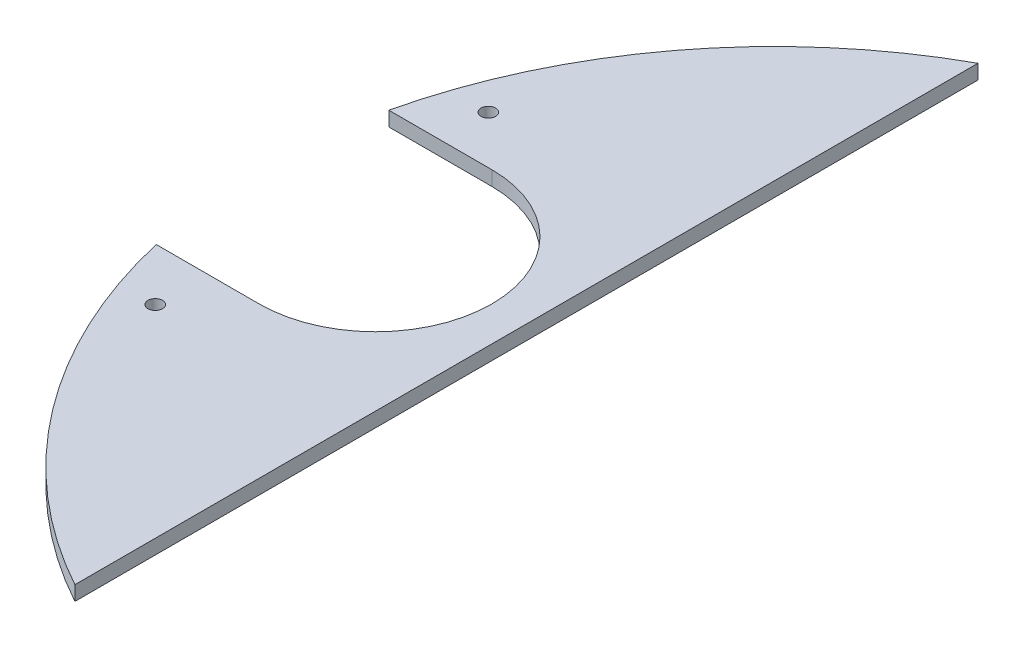
SolidWorks part; units mm, degrees
ref_plane "Front Plane" through (0, 0, 0) normal (0, 0, 1) x (1, 0, 0)
ref_plane "Top Plane" through (0, 0, 0) normal (0, 1, 0) x (1, 0, 0)
ref_plane "Right Plane" through (0, 0, 0) normal (1, 0, 0) x (0, 0, -1)
sketch "Sketch1" plane through (0, 0, 0) normal (0, 1, 0) x (1, 0, 0)
  line L0 (0, -112.5) -> (0, 0) construction
  line L1 (-80, 112.5) -> (100, 112.5)
  line L3 (-80, -112.5) -> (100, -112.5)
  line L4 (100, 112.5) -> (100, -112.5)
  line L5 (0, 0) -> (0, 112.5) construction
  arc A0 (-80, 112.5) -> (-80, -112.5) centre (-80, 0) ccw
  dimension "D1" = 100
  dimension "D4" = 112.5
  dimension "D2" = 80
  dimension "D3" = 225
extrude "Boss-Extrude1" add sketch "Sketch1" against normal blind 3.175
sketch "Sketch2" plane through (0, 0, 0) normal (0, 1, 0) x (1, 0, 0)
  line L0 (36.144, -74.2188) -> (36.144, -67.8688) construction
  line L1 (52.019, 0) -> (52.019, -89.9668) construction
  line L2 (11.887, -89.9668) -> (92.151, -89.9668)
  line L3 (11.887, -89.9668) -> (11.887, -102.9208)
  line L4 (11.887, -102.9208) -> (92.151, -102.9208)
  line L5 (92.151, -89.9668) -> (92.151, -102.9208)
  line L6 (11.887, 89.9668) -> (92.151, 89.9668)
  line L7 (11.887, 89.9668) -> (11.887, 102.9208)
  line L8 (11.887, 102.9208) -> (92.151, 102.9208)
  line L9 (92.151, 89.9668) -> (92.151, 102.9208)
  line L10 (52.019, 0) -> (52.019, 89.9668) construction
  line L11 (36.144, -67.8688) -> (36.144, -61.5188) construction
  line L12 (36.144, -61.5188) -> (36.144, -55.1688) construction
  line L13 (36.144, -55.1688) -> (36.144, -48.8188) construction
  line L14 (36.144, -48.8188) -> (36.144, -42.4688) construction
  line L15 (36.144, -42.4688) -> (36.144, -36.1188) construction
  line L16 (67.894, -74.2188) -> (67.894, -67.8688) construction
  line L17 (67.894, -67.8688) -> (67.894, -61.5188) construction
  line L18 (67.894, -61.5188) -> (67.894, -55.1688) construction
  line L19 (67.894, -55.1688) -> (67.894, -48.8188) construction
  line L20 (67.894, -48.8188) -> (67.894, -42.4688) construction
  line L21 (67.894, -42.4688) -> (67.894, -36.1188) construction
  line L22 (36.144, -74.2188) -> (67.894, -74.2188) construction
  line L23 (36.144, -36.1188) -> (67.894, -36.1188) construction
  line L24 (36.144, 36.1188) -> (36.144, 42.4688) construction
  line L25 (36.144, 42.4688) -> (36.144, 48.8188) construction
  line L26 (36.144, 48.8188) -> (36.144, 55.1688) construction
  line L27 (36.144, 55.1688) -> (36.144, 61.5188) construction
  line L28 (36.144, 61.5188) -> (36.144, 67.8688) construction
  line L29 (36.144, 67.8688) -> (36.144, 74.2188) construction
  line L30 (67.894, 36.1188) -> (67.894, 42.4688) construction
  line L31 (67.894, 42.4688) -> (67.894, 48.8188) construction
  line L32 (67.894, 48.8188) -> (67.894, 55.1688) construction
  line L33 (67.894, 55.1688) -> (67.894, 61.5188) construction
  line L34 (67.894, 61.5188) -> (67.894, 67.8688) construction
  line L35 (67.894, 67.8688) -> (67.894, 74.2188) construction
  line L36 (36.144, 74.2188) -> (67.894, 74.2188) construction
  line L37 (36.144, 36.1188) -> (67.894, 36.1188) construction
  line L38 (36.144, 55.1688) -> (52.019, 55.1688) construction
  line L39 (52.019, 55.1688) -> (67.894, 55.1688) construction
  line L40 (0, -112.5) -> (0, 112.5) construction
  line L41 (0, 0) -> (52.019, 0) construction
  line L42 (100, 112.5) -> (-80, 112.5) construction
  line L43 (-80, -112.5) -> (100, -112.5) construction
  circle A1 centre (36.144, -74.2188) radius 1.5875
  circle A2 centre (36.144, -67.8688) radius 1.5875
  circle A3 centre (36.144, -61.5188) radius 1.5875
  circle A4 centre (36.144, -55.1688) radius 1.5875
  circle A5 centre (36.144, -48.8188) radius 1.5875
  circle A6 centre (36.144, -42.4688) radius 1.5875
  circle A7 centre (36.144, -36.1188) radius 1.5875
  circle A8 centre (67.894, -74.2188) radius 1.5875
  circle A9 centre (67.894, -67.8688) radius 1.5875
  circle A10 centre (67.894, -61.5188) radius 1.5875
  circle A11 centre (67.894, -55.1688) radius 1.5875
  circle A12 centre (67.894, -48.8188) radius 1.5875
  circle A13 centre (67.894, -42.4688) radius 1.5875
  circle A14 centre (67.894, -36.1188) radius 1.5875
  circle A15 centre (36.144, 74.2188) radius 1.5875
  circle A16 centre (36.144, 67.8688) radius 1.5875
  circle A17 centre (36.144, 61.5188) radius 1.5875
  circle A18 centre (36.144, 55.1688) radius 1.5875
  circle A19 centre (36.144, 48.8188) radius 1.5875
  circle A20 centre (36.144, 42.4688) radius 1.5875
  circle A21 centre (36.144, 36.1188) radius 1.5875
  circle A22 centre (67.894, 74.2188) radius 1.5875
  circle A23 centre (67.894, 67.8688) radius 1.5875
  circle A24 centre (67.894, 61.5188) radius 1.5875
  circle A25 centre (67.894, 55.1688) radius 1.5875
  circle A26 centre (67.894, 48.8188) radius 1.5875
  circle A27 centre (67.894, 42.4688) radius 1.5875
  circle A28 centre (67.894, 36.1188) radius 1.5875
  dimension "D6" = 3.175
  dimension "D7" = 6.35
  dimension "D8" = 15.875
  dimension "D10" = 3.175
  dimension "D1" = 12.954
  dimension "D2" = 80.264
  dimension "D3" = 179.9336
  dimension "D4" = 15.748
  dimension "D5" = 15.875
  dimension "D9" = 15.875
  dimension "D11" = 6.35
  dimension "D12" = 15.748
  dimension "D13" = 72.2376
  dimension "D14" = 205.8416
  dimension "D15" = 92.151
extrude "Cut-Extrude1" cut sketch "Sketch2" against normal through all
ref_plane "Plane1" through (92.151, 0, -89.9668) normal (1, 0, 0) x (0, 0, -1)
sketch "Sketch7" plane through (0, 0, 0) normal (0, 1, 0) x (1, 0, 0)
  line L0 (10, 112.5) -> (9.5239, 69.215) construction
  line L1 (-37.4661, 69.215) -> (9.5239, 69.215)
  line L2 (-37.4661, 69.215) -> (-37.4661, -69.215)
  line L3 (-37.4661, -69.215) -> (9.5239, -69.215)
  line L4 (9.5239, 69.215) -> (9.5239, -69.215)
  line L5 (100, 112.5) -> (-80, 112.5) construction
  line L6 (9.5239, -69.215) -> (10, -112.5) construction
  line L7 (-80, -112.5) -> (100, -112.5) construction
  circle A0 centre (-50.1661, 0) radius 1.5875
  circle A1 centre (25.5828, 0) radius 1.5875
  circle A2 centre (87.4621, 0) radius 1.5875
  dimension "D3" = 3.175
  dimension "D1" = 46.99
  dimension "D2" = 138.43
  dimension "D4" = 12.7
extrude "Cut-Extrude4" cut sketch "Sketch7" against normal through all
sketch "Sketch8" plane through (0, 0, 0) normal (0, 1, 0) x (1, 0, 0)
  line L0 (-80, 112.5) -> (-80, -112.5) construction
  line L1 (-192.5, 0) -> (100, 0) construction
  line L2 (100, -112.5) -> (100, 112.5) construction
  line L3 (-167.0966, 25.4) -> (-229.7767, 25.4)
  line L4 (-229.7767, 25.4) -> (-229.7767, -25.4)
  line L5 (-229.7767, -25.4) -> (-167.0966, -25.4)
  arc A0 (-80, 112.5) -> (-80, -112.5) centre (-80, 0) ccw construction
  arc A2 (-167.0966, 25.4) -> (-167.0966, -25.4) centre (-167.0966, 0) cw
  point P12 (-80, 0)
  dimension "D2" = 87.0966
  dimension "D1" = 25.4
extrude "Cut-Extrude5" cut sketch "Sketch8" against normal through all
sketch "Sketch9" plane through (0, 0, 0) normal (0, 1, 0) x (1, 0, 0)
  line L1 (-134.1365, 167.1829) -> (165.9358, 167.1829)
  line L2 (-134.1365, 167.1829) -> (-134.1365, -166.8432)
  line L3 (-134.1365, -166.8432) -> (165.9358, -166.8432)
  line L4 (165.9358, 167.1829) -> (165.9358, -166.8432)
extrude "Cut-Extrude6" cut sketch "Sketch9" against normal through all
sketch "Sketch10" plane through (0, 0, 0) normal (0, 1, 0) x (1, 0, 0)
  circle A0 centre (-178.3459, -36.8647) radius 1.5875
  circle A1 centre (-178.3459, 35.8859) radius 1.5875
  dimension "D1" = 3.175
  dimension "D2" = 3.175
extrude "Cut-Extrude7" cut sketch "Sketch10" against normal through all
